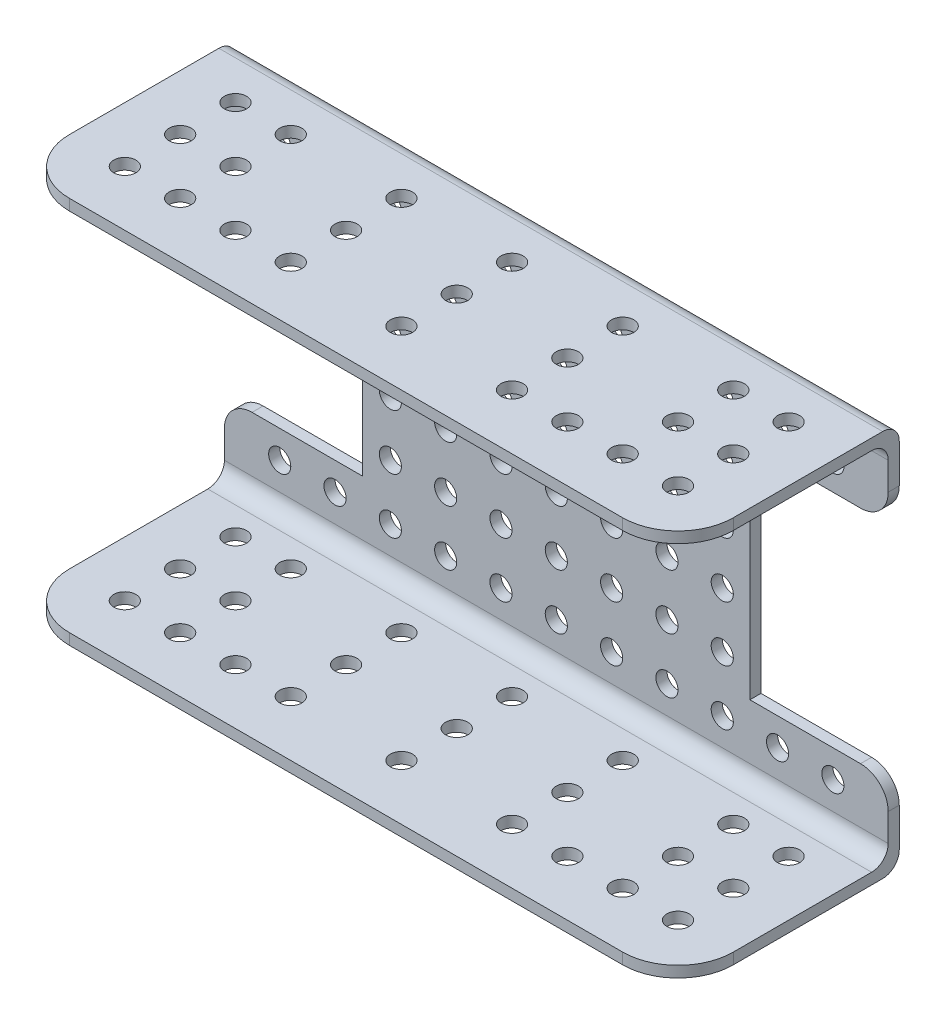
SolidWorks part; units mm, degrees
material "6061-T6 (SS)"
ref_plane "Ön Düzlem" through (0, 0, 0) normal (0, 0, 1) x (1, 0, 0)
ref_plane "Üst Düzlem" through (0, 0, 0) normal (0, 1, 0) x (1, 0, 0)
ref_plane "Sağ Düzlem" through (0, 0, 0) normal (1, 0, 0) x (0, 0, -1)
sketch "Çizim1" plane through (0, 0, 0) normal (0, 0, 1) x (1, 0, 0)
  line L0 (-60, 20) -> (-35, 20)
  line L1 (-60, 35) -> (60, 35)
  line L2 (-60, 35) -> (-60, 20)
  line L3 (-60, -35) -> (60, -35)
  line L4 (60, 35) -> (60, 20)
  line L5 (-35, 20) -> (-35, -20)
  line L6 (-35, -20) -> (-60, -20)
  line L7 (-60, -20) -> (-60, -35)
  line L8 (60, 20) -> (35, 20)
  line L9 (35, 20) -> (35, -20)
  line L10 (35, -20) -> (60, -20)
  line L11 (60, -20) -> (60, -35)
  line L12 (-60, -35) -> (60, 35) construction
  dimension "D1" = 120
  dimension "D2" = 70
  dimension "D3" = 25
  dimension "D4" = 15
  dimension "D5" = 15
  dimension "D6" = 15
  dimension "D7" = 15
  dimension "D8" = 25
extrude "Yükseklik-Ekstrüzyon1" add sketch "Çizim1" along normal blind 2
sketch "Çizim2" plane through (0, 0, 2) normal (0, 0, 1) x (1, 0, 0)
  line L0 (60, 20) -> (60, 35) construction
  line L1 (-60, 35) -> (60, 35)
  line L2 (-60, 35) -> (-60, 33)
  line L3 (-60, 33) -> (60, 33)
  line L4 (60, 35) -> (60, 33)
  line L5 (-60, -20) -> (-60, -35) construction
  line L6 (-60, -33) -> (60, -33)
  line L7 (-60, -33) -> (-60, -35)
  line L8 (-60, -35) -> (60, -35)
  line L9 (60, -33) -> (60, -35)
  dimension "D1" = 2
  dimension "D2" = 2
extrude "Yükseklik-Ekstrüzyon2" add sketch "Çizim2" along normal blind 38
fillet "Radyus1" radius 10 4 edges at (-60, 34, 40) (60, 34, 40) (60, -34, 40) (-60, -34, 40)
fillet "Radyus2" radius 5 4 edges at (60, -20, 1) (60, 20, 1) (-60, -20, 1) (-60, 20, 1)
sketch "Çizim3" plane through (0, 0, 0) normal (0, 0, -1) x (-1, 0, 0)
  line L0 (60, -35) -> (-60, -35) construction
  line L1 (35, 20) -> (35, -20) construction
  circle A0 centre (30, -25) radius 2
  circle A1 centre (40, -25) radius 2
  circle A2 centre (50, -25) radius 2
  circle A3 centre (20, -25) radius 2
  circle A4 centre (10, -25) radius 2
  circle A5 centre (0, -25) radius 2
  circle A6 centre (-10, -25) radius 2
  circle A7 centre (-20, -25) radius 2
  circle A8 centre (-30, -25) radius 2
  circle A9 centre (20, -15) radius 2
  circle A10 centre (10, -15) radius 2
  circle A11 centre (0, -15) radius 2
  circle A12 centre (-10, -15) radius 2
  circle A13 centre (-20, -15) radius 2
  circle A14 centre (-30, -15) radius 2
  circle A15 centre (20, -5) radius 2
  circle A16 centre (10, -5) radius 2
  circle A17 centre (0, -5) radius 2
  circle A18 centre (-10, -5) radius 2
  circle A19 centre (-20, -5) radius 2
  circle A20 centre (-30, -5) radius 2
  circle A21 centre (20, 5) radius 2
  circle A22 centre (10, 5) radius 2
  circle A23 centre (0, 5) radius 2
  circle A24 centre (-10, 5) radius 2
  circle A25 centre (-20, 5) radius 2
  circle A26 centre (-30, 5) radius 2
  circle A27 centre (20, 15) radius 2
  circle A28 centre (10, 15) radius 2
  circle A29 centre (0, 15) radius 2
  circle A30 centre (-10, 15) radius 2
  circle A31 centre (-20, 15) radius 2
  circle A32 centre (-30, 15) radius 2
  circle A33 centre (20, 25) radius 2
  circle A34 centre (10, 25) radius 2
  circle A35 centre (0, 25) radius 2
  circle A36 centre (-10, 25) radius 2
  circle A37 centre (-20, 25) radius 2
  circle A38 centre (-30, 25) radius 2
  circle A39 centre (30, -15) radius 2
  circle A40 centre (30, -5) radius 2
  circle A41 centre (30, 5) radius 2
  circle A42 centre (30, 15) radius 2
  circle A43 centre (30, 25) radius 2
  circle A44 centre (40, 25) radius 2
  circle A45 centre (50, 25) radius 2
  circle A46 centre (-40, 25) radius 2
  circle A47 centre (-50, 25) radius 2
  circle A48 centre (-40, -25) radius 2
  circle A49 centre (-50, -25) radius 2
  dimension "D1" = 4
  dimension "D2" = 10
  dimension "D3" = 5
  dimension "D5" = 7
  dimension "D4" = 3
  dimension "D6" = 6
  dimension "D7" = 3
  dimension "D8" = 3
  dimension "D9" = 3
extrude "Kes-Ekstrüzyon1" cut sketch "Çizim3" against normal up to next (2 mm away)
fillet "Radyus3" radius 3 4 edges at (0, 35, 0) (0, -33, 2) (0, -35, 0)
sketch "Çizim4" plane through (0, -35, 0) normal (0, -1, 0) x (1, 0, 0)
  line L2 (60, 0) -> (-60, 0) construction
  line L3 (-60, 30) -> (-60, 3) construction
  line L7 (-50, 40) -> (50, 40) construction
  circle A0 centre (0, 10) radius 2
  circle A1 centre (20, 10) radius 2
  circle A2 centre (40, 10) radius 2
  circle A3 centre (20, 20) radius 2
  circle A4 centre (40, 20) radius 2
  circle A5 centre (20, 30) radius 2
  circle A6 centre (40, 30) radius 2
  circle A7 centre (0, 20) radius 2
  circle A8 centre (0, 30) radius 2
  circle A9 centre (-20, 10) radius 2
  circle A10 centre (-40, 10) radius 2
  circle A11 centre (-40, 20) radius 2
  circle A12 centre (-40, 30) radius 2
  circle A13 centre (-20, 20) radius 2
  circle A14 centre (-20, 30) radius 2
  circle A15 centre (30, 30) radius 2
  circle A16 centre (-30, 30) radius 2
  circle A17 centre (50, 10) radius 2
  circle A18 centre (50, 20) radius 2
  circle A19 centre (50, 30) radius 2
  circle A20 centre (-50, 10) radius 2
  circle A21 centre (-50, 20) radius 2
  circle A22 centre (-50, 30) radius 2
  point P2 (0, 0)
  dimension "D1" = 4
  dimension "D2" = 10
  dimension "D3" = 60
  dimension "D4" = 3
  dimension "D6" = 2
  dimension "D9" = 4
  dimension "D10" = 10
  dimension "D11" = 10
  dimension "D12" = 10
  dimension "D13" = 4
  dimension "D14" = 10
  dimension "D5" = 3
  dimension "D7" = 2
  dimension "D8" = 3
  dimension "D15" = 2
  dimension "D16" = 2
extrude "Kes-Ekstrüzyon2" cut sketch "Çizim4" against normal through all
